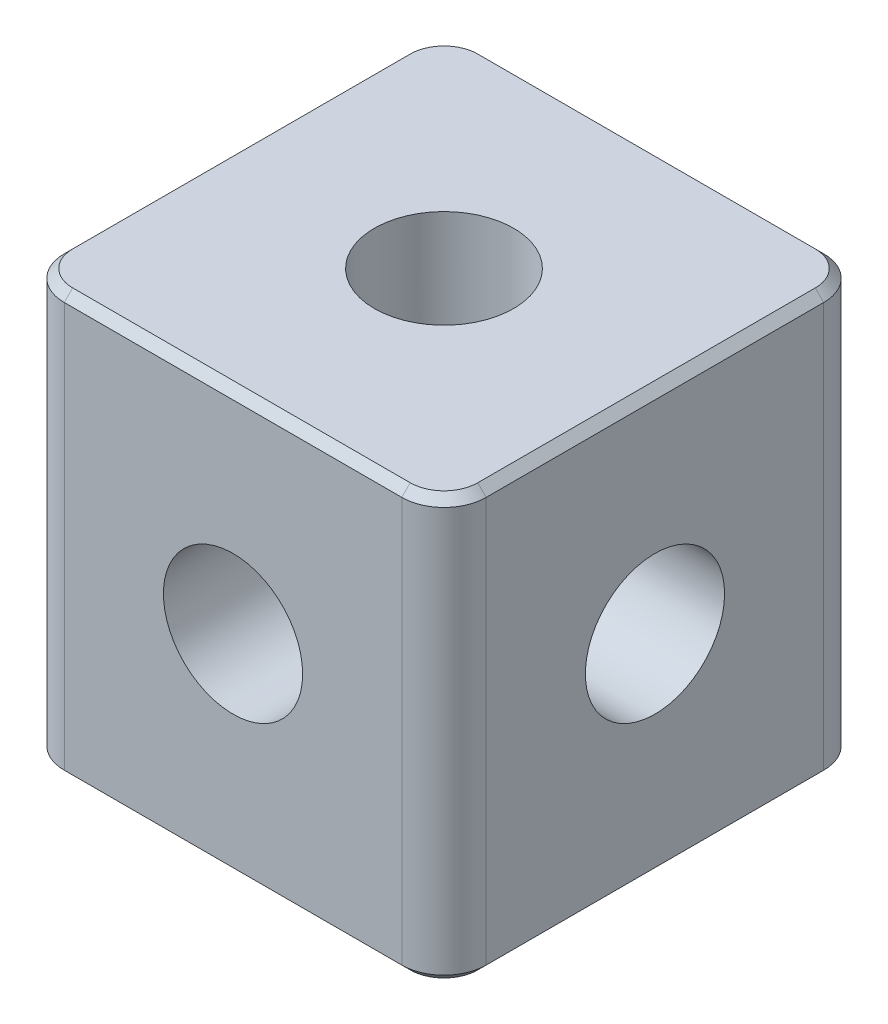
SolidWorks part; units mm, degrees
material "6061 合金"
ref_plane "前视基准面" through (0, 0, 0) normal (0, 0, 1) x (1, 0, 0)
ref_plane "上视基准面" through (0, 0, 0) normal (0, 1, 0) x (1, 0, 0)
ref_plane "右视基准面" through (0, 0, 0) normal (1, 0, 0) x (0, 0, -1)
sketch "草图1" plane through (0, 0, 0) normal (0, 1, 0) x (1, 0, 0)
  line L1 (-5, -5) -> (5, -5)
  line L2 (-5, -5) -> (-5, 5)
  line L3 (-5, 5) -> (5, 5)
  line L4 (5, -5) -> (5, 5)
  line L5 (0, 5) -> (0, -5) construction
  line L6 (-5, 0) -> (5, 0) construction
  point P0 (0, 0)
  dimension "D1" = 10
extrude "凸台-拉伸1" add sketch "草图1" along normal mid plane 10
hole_wizard "M4 螺纹孔1" positions "草图2" profile "草图3" tap size "M4" standard "GB" end condition through all
sketch "草图2" plane through (0, 5, 0) normal (0, 1, 0) x (1, 0, 0)
  point P0 (0, 0)
sketch "草图3" plane through (0, 5, 0) normal (1, 0, 0) x (0, 0, 1)
  line L0 (0, 0) -> (0, 10)
  line L1 (0, 10) -> (1.65, 10)
  line L2 (1.65, 10) -> (1.65, 0)
  line L5 (1.65, 0) -> (0, 0)
  line L11 (0, -6.35) -> (0, 107.95) construction
  dimension "通孔螺纹孔钻头直径" = 3.3
  dimension "通孔螺纹孔钻头深度" = 10
cosmetic thread "孔螺蚊线1"
hole_wizard "M4 螺纹孔3" positions "草图4" profile "草图5" tap size "M4" standard "GB" end condition through all
sketch "草图4" plane through (0, 0, 5) normal (0, 0, 1) x (1, 0, 0)
  point P0 (0, 0)
sketch "草图5" plane through (0, 0, 5) normal (1, 0, 0) x (0, -1, 0)
  line L0 (0, 0) -> (0, 10)
  line L1 (0, 10) -> (1.65, 10)
  line L2 (1.65, 10) -> (1.65, 0)
  line L5 (1.65, 0) -> (0, 0)
  line L11 (0, -6.35) -> (0, 107.95) construction
  dimension "通孔螺纹孔钻头直径" = 3.3
  dimension "通孔螺纹孔钻头深度" = 10
cosmetic thread "孔螺蚊线2"
hole_wizard "M4 螺纹孔2" positions "草图6" profile "草图7" tap size "M4" standard "GB" end condition through all
sketch "草图6" plane through (5, 0, 0) normal (1, 0, 0) x (0, 0, -1)
  point P0 (0, 0)
sketch "草图7" plane through (5, 0, 0) normal (0, 1, 0) x (0, 0, -1)
  line L0 (0, 0) -> (0, 10)
  line L1 (0, 10) -> (1.65, 10)
  line L2 (1.65, 10) -> (1.65, 0)
  line L5 (1.65, 0) -> (0, 0)
  line L11 (0, -6.35) -> (0, 107.95) construction
  dimension "通孔螺纹孔钻头直径" = 3.3
  dimension "通孔螺纹孔钻头深度" = 10
cosmetic thread "孔螺蚊线3"
fillet "圆角1" radius 1 4 edges at (5, 0, -5) (5, 0, 5) (-5, 0, 5) (-5, 0, -5)
chamfer "倒角1" distance 0.2 angle 45 16 edges at (5, -5, 0) (4.7071, -5, -4.7071) (4.7071, -5, 4.7071) (0, -5, -5) (0, -5, 5) (-4.7071, -5, -4.7071) (-4.7071, -5, 4.7071) (-5, -5, 0) (5, 5, 0) (4.7071, 5, -4.7071) (4.7071, 5, 4.7071) (0, 5, -5) (0, 5, 5) (-4.7071, 5, -4.7071) (-4.7071, 5, 4.7071) (-5, 5, 0)
